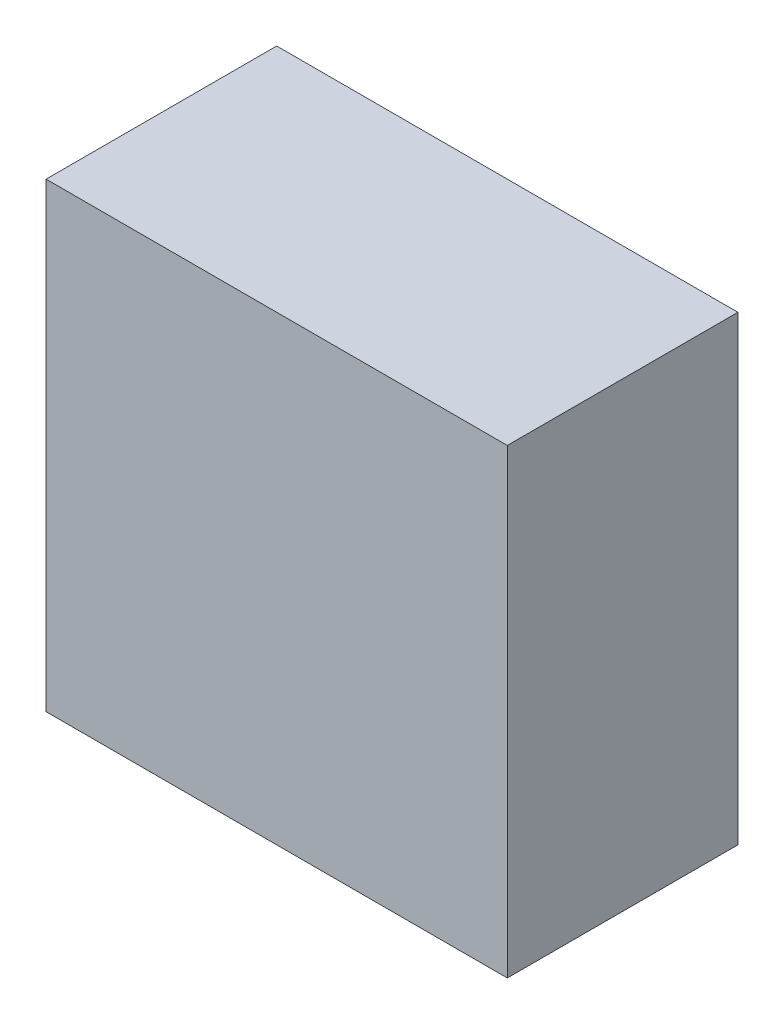
SolidWorks part; units mm, degrees
ref_plane "Front Plane" through (0, 0, 0) normal (0, 0, 1) x (1, 0, 0)
ref_plane "Top Plane" through (0, 0, 0) normal (0, 1, 0) x (1, 0, 0)
ref_plane "Right Plane" through (0, 0, 0) normal (1, 0, 0) x (0, 0, -1)
sketch "Sketch1" plane through (0, 0, 0) normal (0, 0, 1) x (1, 0, 0)
  line L1 (-35.3588, -24.9525) -> (-15.3588, -24.9525)
  line L2 (-35.3588, -24.9525) -> (-35.3588, -44.9525)
  line L3 (-35.3588, -44.9525) -> (-15.3588, -44.9525)
  line L4 (-15.3588, -24.9525) -> (-15.3588, -44.9525)
  dimension "D1" = 20
  dimension "D2" = 20
extrude "Boss-Extrude1" add sketch "Sketch1" along normal blind 10
